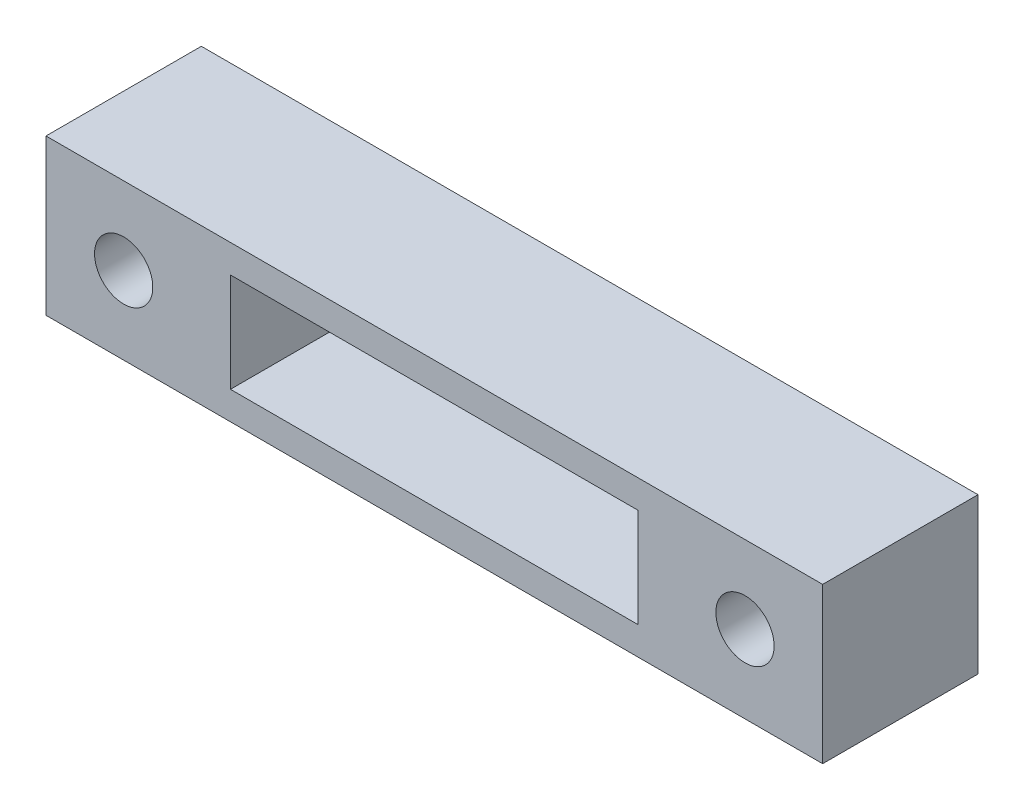
SolidWorks part; units mm, degrees
ref_plane "Front Plane" through (0, 0, 0) normal (0, 0, 1) x (1, 0, 0)
ref_plane "Top Plane" through (0, 0, 0) normal (0, 1, 0) x (1, 0, 0)
ref_plane "Right Plane" through (0, 0, 0) normal (1, 0, 0) x (0, 0, -1)
sketch "Sketch1" plane through (0, 0, 0) normal (0, 1, 0) x (1, 0, 0)
  line L1 (-20, -20) -> (20, -20)
  line L2 (-20, -20) -> (-20, 20)
  line L3 (-20, 20) -> (20, 20)
  line L4 (20, -20) -> (20, 20)
  line L5 (-20, -20) -> (20, 20) construction
  line L6 (-20, 20) -> (20, -20) construction
  line L7 (-10.5, -17.5) -> (10.5, -17.5)
  line L8 (-10.5, -17.5) -> (-10.5, 17.5)
  line L9 (-10.5, 17.5) -> (10.5, 17.5)
  line L10 (10.5, -17.5) -> (10.5, 17.5)
  line L11 (-10.5, -17.5) -> (10.5, 17.5) construction
  line L12 (-10.5, 17.5) -> (10.5, -17.5) construction
  line L13 (-20, 20) -> (20, 20)
  line L14 (-20, 20) -> (-20, 12)
  line L15 (-20, 12) -> (20, 12)
  line L16 (20, 20) -> (20, 12)
  point P0 (0, 0)
  point P6 (0, 0)
  point P13 (-10.5, 17.5)
  dimension "D1" = 40
  dimension "D2" = 40
  dimension "D3" = 35
  dimension "D4" = 21
  dimension "D5" = 8
extrude "Boss-Extrude1" add sketch "Sketch1" along normal blind 8 contours L2 L15 L8 L9 L10 L4 L3 | L8 L15 L10 L9
sketch "Sketch2" plane through (0, 0, -12) normal (0, 0, 1) x (1, 0, 0)
  line L1 (0, 0) -> (0, 8)
  line L2 (-20, 0) -> (20, 0) construction
  line L3 (-20, 8) -> (20, 8) construction
  line L4 (-10.5, 1.45) -> (10.5, 1.45)
  line L5 (-10.5, 1.45) -> (-10.5, 6.55)
  line L6 (-10.5, 6.55) -> (10.5, 6.55)
  line L7 (10.5, 1.45) -> (10.5, 6.55)
  line L8 (-10.5, 1.45) -> (10.5, 6.55) construction
  line L9 (-10.5, 6.55) -> (10.5, 1.45) construction
  point P1 (0, 4)
  dimension "D1" = 5.1
  dimension "D2" = 21
extrude "Cut-Extrude1" cut sketch "Sketch2" against normal blind 5.5 contours L5 L6 L7 L4
sketch "Sketch4" plane through (0, 0, -17.5) normal (0, 0, 1) x (1, 0, 0)
  line L0 (0, 0) -> (0, 8)
  line L1 (-20, 8) -> (20, 8) construction
  line L3 (-9, 2.5) -> (9, 2.5)
  line L4 (-9, 2.5) -> (-9, 5.5)
  line L5 (-9, 5.5) -> (9, 5.5)
  line L6 (9, 2.5) -> (9, 5.5)
  line L7 (-9, 2.5) -> (9, 5.5) construction
  line L8 (-9, 5.5) -> (9, 2.5) construction
  point P5 (0, 4)
  dimension "D1" = 3
  dimension "D2" = 18
extrude "Cut-Extrude2" cut sketch "Sketch4" against normal blind 5.5 contours L3 L6 L5 L4
sketch "Sketch5" plane through (0, 0, -20) normal (0, 0, -1) x (-1, 0, 0)
  circle A0 centre (-16, 4) radius 1.5
  circle A1 centre (16, 4) radius 1.5
extrude "Cut-Extrude3" cut sketch "Sketch5" against normal blind 10.5
